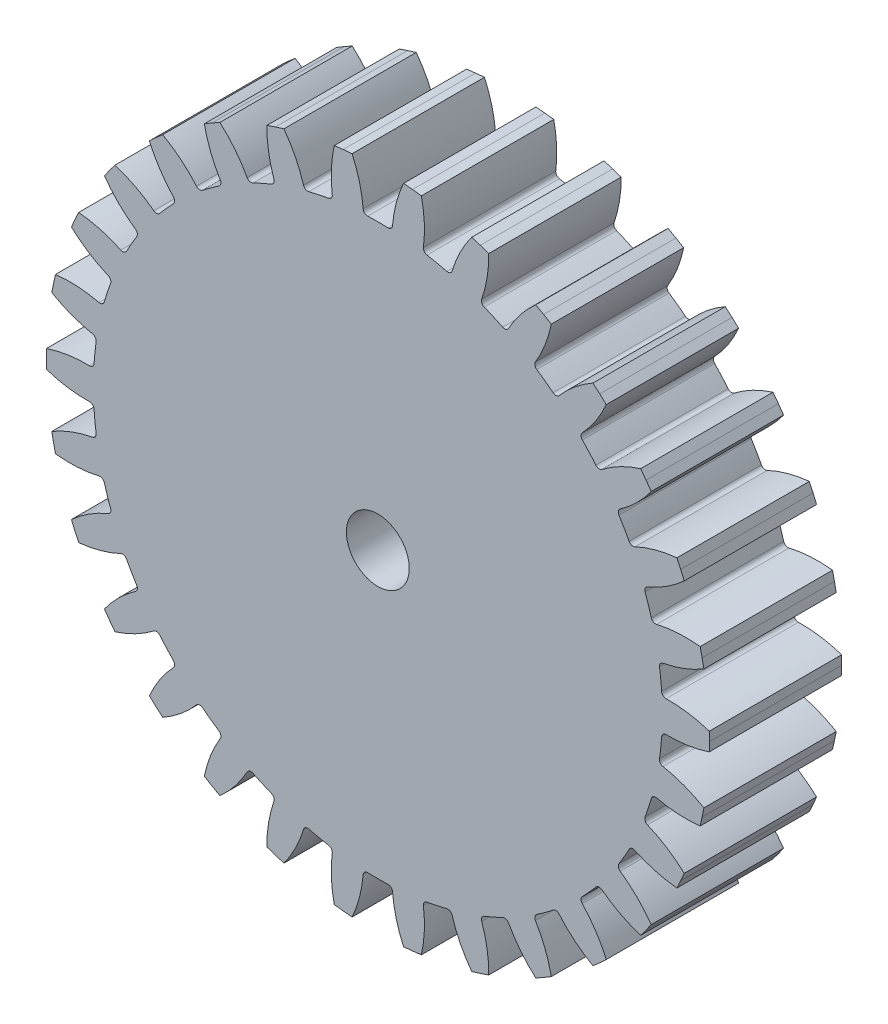
SolidWorks part; units mm, degrees
ref_plane "Front Plane" through (0, 0, 0) normal (0, 0, 1) x (1, 0, 0)
ref_plane "Top Plane" through (0, 0, 0) normal (0, 1, 0) x (1, 0, 0)
ref_plane "Right Plane" through (0, 0, 0) normal (1, 0, 0) x (0, 0, -1)
sketch "Sketch1" plane through (0, 0, 0) normal (0, 0, 1) x (1, 0, 0)
  line L0 (0, 0) -> (74.4139, 0) construction
  line L1 (0, 0) -> (21.3748, 2.2466) construction
  line L2 (0, 0) -> (74.4139, 4.0301) construction
  line L3 (0, 0) -> (74.4139, 2.0136) construction
  line L4 (25.0408, 0.6776) -> (25.05, 0)
  line L5 (0, 0) -> (21.3748, -2.2466) construction
  line L6 (0, 0) -> (21.3748, 2.2466)
  line L7 (0, 0) -> (21.3748, -2.2466) construction
  line L8 (0, 0) -> (21.3748, -2.2466)
  line L9 (25.0408, -0.6776) -> (25.05, 0)
  circle A0 centre (0, 0) radius 25.05 construction
  circle A1 centre (0, 0) radius 23.3875 construction
  circle A2 centre (0, 0) radius 21.4925 construction
  arc A3 (21.461, 1.1623) -> (25.0408, 0.6776) centre (21.9818, -8.4533) cw
  arc A4 (21.461, 1.1623) -> (21.3748, 2.2466) centre (0, 0) ccw
  arc A5 (21.461, -1.1623) -> (21.3748, -2.2466) centre (0, 0) cw
  arc A6 (21.461, -1.1623) -> (25.0408, -0.6776) centre (21.9818, 8.4533) ccw
  dimension "D1" = 50.1
  dimension "D2" = 1.6625
  dimension "D7" = 1.895
  dimension "D4" = 6
  dimension "D5" = 3.1
  dimension "D6" = 1.55
extrude "Boss-Extrude1" add sketch "Sketch1" along normal blind 10
fillet "Fillet1" radius 0.3325 2 edges at (21.461, 1.1623, 5) (21.461, -1.1623, 5)
pattern_circular "CirPattern1" count 30 over 360 about axis through (0, 0, 0) along (0, 0, 1) of "Boss-Extrude1", "Fillet1"
sketch "Sketch2" plane through (0, 0, 0) normal (0, 0, -1) x (-1, 0, 0)
  circle A0 centre (0, 0) radius 2.375
  dimension "D1" = 4.75
extrude "Cut-Extrude1" cut sketch "Sketch2" against normal up to next
